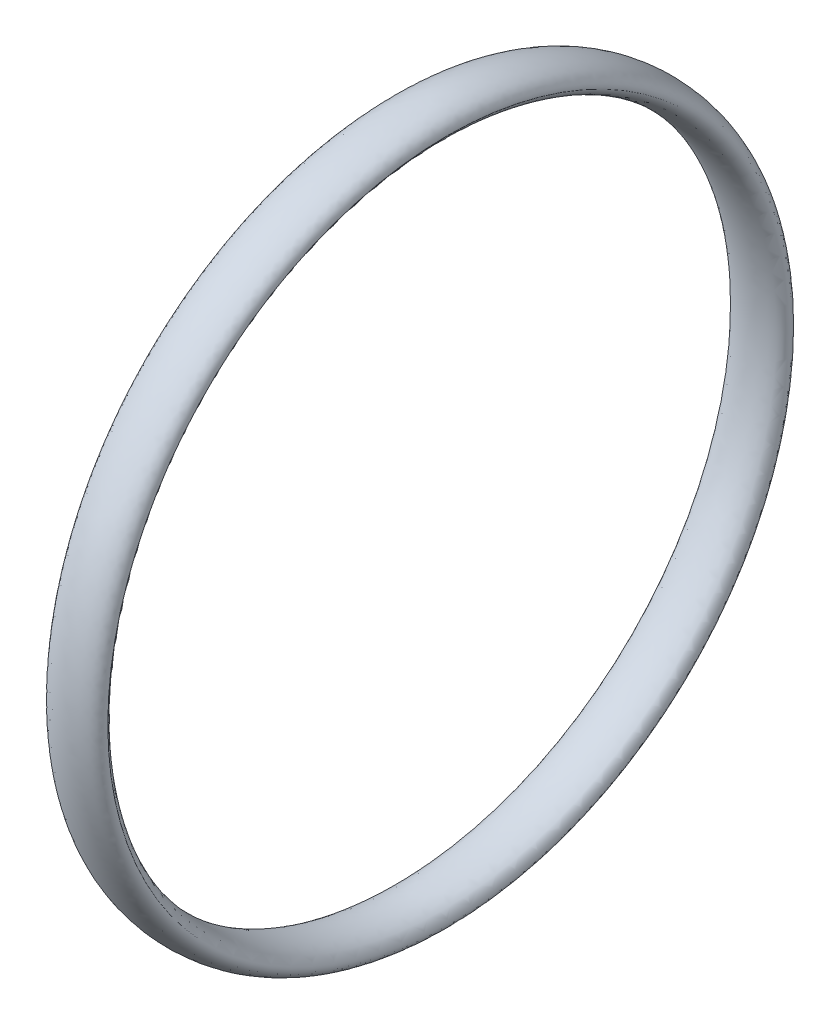
SolidWorks part; units mm, degrees
ref_plane "Front Plane" through (0, 0, 0) normal (0, 0, 1) x (1, 0, 0)
ref_plane "Top Plane" through (0, 0, 0) normal (0, 1, 0) x (1, 0, 0)
ref_plane "Right Plane" through (0, 0, 0) normal (1, 0, 0) x (0, 0, -1)
sketch "Sketch1" plane through (0, 0, 0) normal (0, 1, 0) x (1, 0, 0)
  line L0 (-1000, 0) -> (49000, 0) construction
  line L1 (0, -1000) -> (0, 49000) construction
  ellipse E0 centre (0, 16.5608) end of major axis (1.3653, 16.5608) minor radius 0.6858
  dimension "D1" = 16.5608
  dimension "D2" = 1.3716
  dimension "D3" = 2.7305
revolve "Revolve1" add sketch "Sketch1" angle 360 about L0
